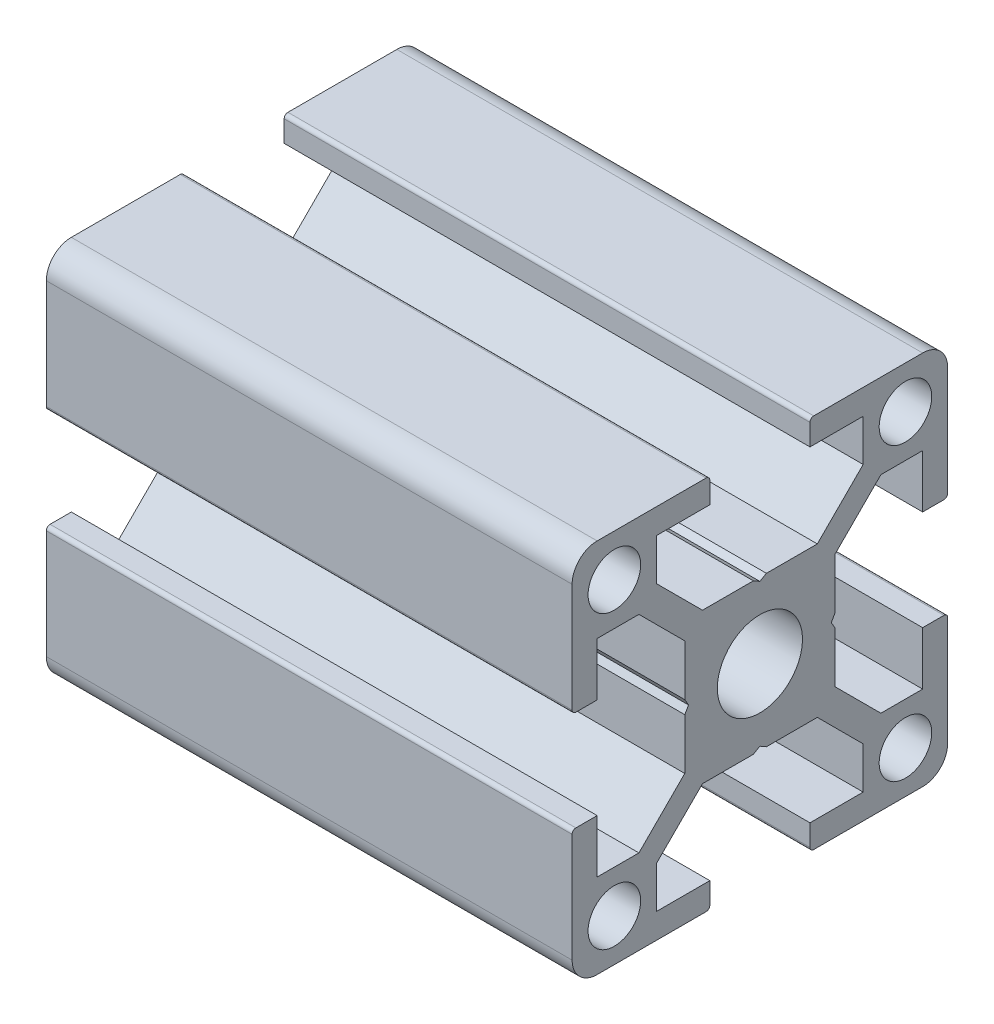
SolidWorks part; units mm, degrees
ref_plane "Front Plane" through (0, 0, 0) normal (0, 0, 1) x (1, 0, 0)
ref_plane "Top Plane" through (0, 0, 0) normal (0, 1, 0) x (1, 0, 0)
ref_plane "Right Plane" through (0, 0, 0) normal (1, 0, 0) x (0, 0, -1)
sketch "Sketch2" plane through (0, 0, 0) normal (0, 0, 1) x (1, 0, 0)
  line L0 (0, 0) -> (42, 0)
  dimension "D1" = 42
other "30xs6 30X30S6(1)"
ref_plane "Plane1" through (0, 0, 0) normal (1, 0, 0) x (0, 1, 0)
sketch "草图1" plane through (0, 0, 0) normal (1, 0, 0) x (0, 1, 0)
  line L0 (-14.7, 4) -> (-13, 4)
  line L1 (-13, 4) -> (-13, 8.25)
  line L2 (-13, 8.25) -> (-9.6642, 8.25)
  line L3 (-9.6642, 8.25) -> (-6, 4.5858)
  line L4 (-6, 4.5858) -> (-6, 0.5196)
  line L5 (-6, 0.5196) -> (-5.7, 0)
  line L6 (-5.7, 0) -> (-6, -0.5196)
  line L7 (-6, -0.5196) -> (-6, -4.5858)
  line L8 (-6, -4.5858) -> (-9.6642, -8.25)
  line L9 (-9.6642, -8.25) -> (-13, -8.25)
  line L10 (-13, -8.25) -> (-13, -4)
  line L11 (-13, -4) -> (-14.7, -4)
  line L12 (-15, -4.3) -> (-15, -13)
  line L13 (-13, -15) -> (-4.3, -15)
  line L14 (-4, -14.7) -> (-4, -13)
  line L15 (-4, -13) -> (-8.25, -13)
  line L16 (-8.25, -13) -> (-8.25, -9.6642)
  line L17 (-8.25, -9.6642) -> (-4.5858, -6)
  line L18 (-4.5858, -6) -> (-0.5196, -6)
  line L19 (-0.5196, -6) -> (0, -5.7)
  line L20 (0, -5.7) -> (0.5196, -6)
  line L21 (0.5196, -6) -> (4.5858, -6)
  line L22 (4.5858, -6) -> (8.25, -9.6642)
  line L23 (8.25, -9.6642) -> (8.25, -13)
  line L24 (8.25, -13) -> (4, -13)
  line L25 (4, -13) -> (4, -14.7)
  line L26 (4.3, -15) -> (13, -15)
  line L27 (15, -13) -> (15, -4.3)
  line L28 (14.7, -4) -> (13, -4)
  line L29 (13, -4) -> (13, -8.25)
  line L30 (13, -8.25) -> (9.6642, -8.25)
  line L31 (9.6642, -8.25) -> (6, -4.5858)
  line L32 (6, -4.5858) -> (6, -0.5196)
  line L33 (6, -0.5196) -> (5.7, 0)
  line L34 (5.7, 0) -> (6, 0.5196)
  line L35 (6, 0.5196) -> (6, 4.5858)
  line L36 (6, 4.5858) -> (9.6642, 8.25)
  line L37 (9.6642, 8.25) -> (13, 8.25)
  line L38 (13, 8.25) -> (13, 4)
  line L39 (13, 4) -> (14.7, 4)
  line L40 (15, 4.3) -> (15, 13)
  line L41 (13, 15) -> (4.3, 15)
  line L42 (4, 14.7) -> (4, 13)
  line L43 (4, 13) -> (8.25, 13)
  line L44 (8.25, 13) -> (8.25, 9.6642)
  line L45 (8.25, 9.6642) -> (4.5858, 6)
  line L46 (4.5858, 6) -> (0.5196, 6)
  line L47 (0.5196, 6) -> (0, 5.7)
  line L48 (0, 5.7) -> (-0.5196, 6)
  line L49 (-0.5196, 6) -> (-4.5858, 6)
  line L50 (-4.5858, 6) -> (-8.25, 9.6642)
  line L51 (-8.25, 9.6642) -> (-8.25, 13)
  line L52 (-8.25, 13) -> (-4, 13)
  line L53 (-4, 13) -> (-4, 14.7)
  line L54 (-4.3, 15) -> (-13, 15)
  line L55 (-15, 13) -> (-15, 4.3)
  arc A0 (-15, 4.3) -> (-14.7, 4) centre (-14.7, 4.3) ccw
  arc A1 (-14.7, -4) -> (-15, -4.3) centre (-14.7, -4.3) ccw
  arc A2 (-15, -13) -> (-13, -15) centre (-13, -13) ccw
  arc A3 (-4.3, -15) -> (-4, -14.7) centre (-4.3, -14.7) ccw
  arc A4 (4, -14.7) -> (4.3, -15) centre (4.3, -14.7) ccw
  arc A5 (13, -15) -> (15, -13) centre (13, -13) ccw
  arc A6 (15, -4.3) -> (14.7, -4) centre (14.7, -4.3) ccw
  arc A7 (14.7, 4) -> (15, 4.3) centre (14.7, 4.3) ccw
  arc A8 (15, 13) -> (13, 15) centre (13, 13) ccw
  arc A9 (4.3, 15) -> (4, 14.7) centre (4.3, 14.7) ccw
  arc A10 (-4, 14.7) -> (-4.3, 15) centre (-4.3, 14.7) ccw
  arc A11 (-13, 15) -> (-15, 13) centre (-13, 13) ccw
  circle A12 centre (11.625, 11.625) radius 2.1
  circle A13 centre (11.625, -11.625) radius 2.1
  circle A14 centre (0, 0) radius 3.4
  circle A15 centre (-11.625, -11.625) radius 2.1
  circle A16 centre (-11.625, 11.625) radius 2.1
  point P90 (-15, 15)
  point P91 (-0.2598, 14.9121)
  point P92 (15, 15)
  point P93 (15, 0)
  point P94 (15, -15)
  point P95 (0.2598, -15)
  point P96 (-15, -15)
  point P97 (-15, 0)
  point P98 (0, 0)
